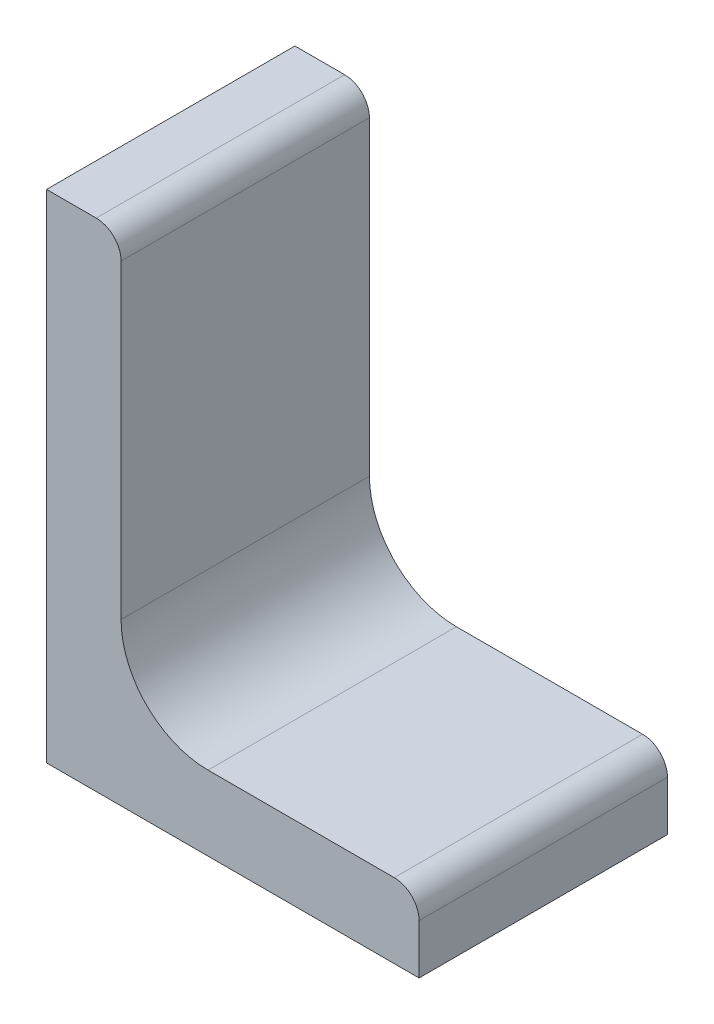
SolidWorks part; units mm, degrees
material "普通碳钢"
ref_plane "前视基准面" through (0, 0, 0) normal (0, 0, 1) x (1, 0, 0)
ref_plane "上视基准面" through (0, 0, 0) normal (0, 1, 0) x (1, 0, 0)
ref_plane "右视基准面" through (0, 0, 0) normal (1, 0, 0) x (0, 0, -1)
sketch "草图1" plane through (0, 0, 0) normal (0, 0, -1) x (-1, 0, 0)
  line L0 (0, 20) -> (0, 0)
  line L1 (0, 0) -> (-15, 0)
  line L2 (-15, 0) -> (-15, 3)
  line L3 (-15, 3) -> (-3, 3)
  line L4 (-3, 3) -> (-3, 20)
  line L5 (-3, 20) -> (0, 20)
  dimension "D1" = 20
  dimension "D2" = 15
  dimension "D3" = 3
extrude "凸台-拉伸1" add sketch "草图1" against normal blind 10
fillet "圆角1" radius 1 2 edges at (15, 3, 5) (3, 20, 5)
fillet "圆角2" radius 3.5 1 edges at (3, 3, 5)
